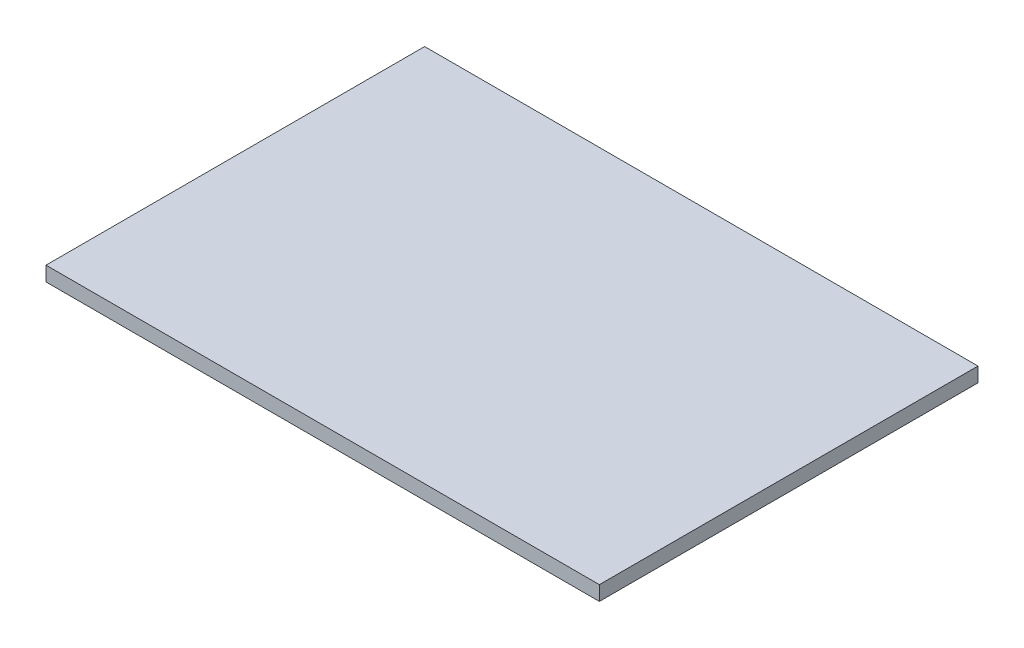
SolidWorks part; units mm, degrees
ref_plane "Front Plane" through (0, 0, 0) normal (0, 0, 1) x (1, 0, 0)
ref_plane "Top Plane" through (0, 0, 0) normal (0, 1, 0) x (1, 0, 0)
ref_plane "Right Plane" through (0, 0, 0) normal (1, 0, 0) x (0, 0, -1)
sketch "Sketch1" plane through (0, 0, 0) normal (0, 1, 0) x (1, 0, 0)
  line L1 (-95, 65) -> (95, 65)
  line L2 (-95, 65) -> (-95, -65)
  line L3 (-95, -65) -> (95, -65)
  line L4 (95, 65) -> (95, -65)
  line L5 (-95, 65) -> (95, -65) construction
  line L6 (-95, -65) -> (95, 65) construction
  point P0 (0, 0)
  dimension "D1" = 130
  dimension "D2" = 190
extrude "Boss-Extrude1" add sketch "Sketch1" along normal blind 5
